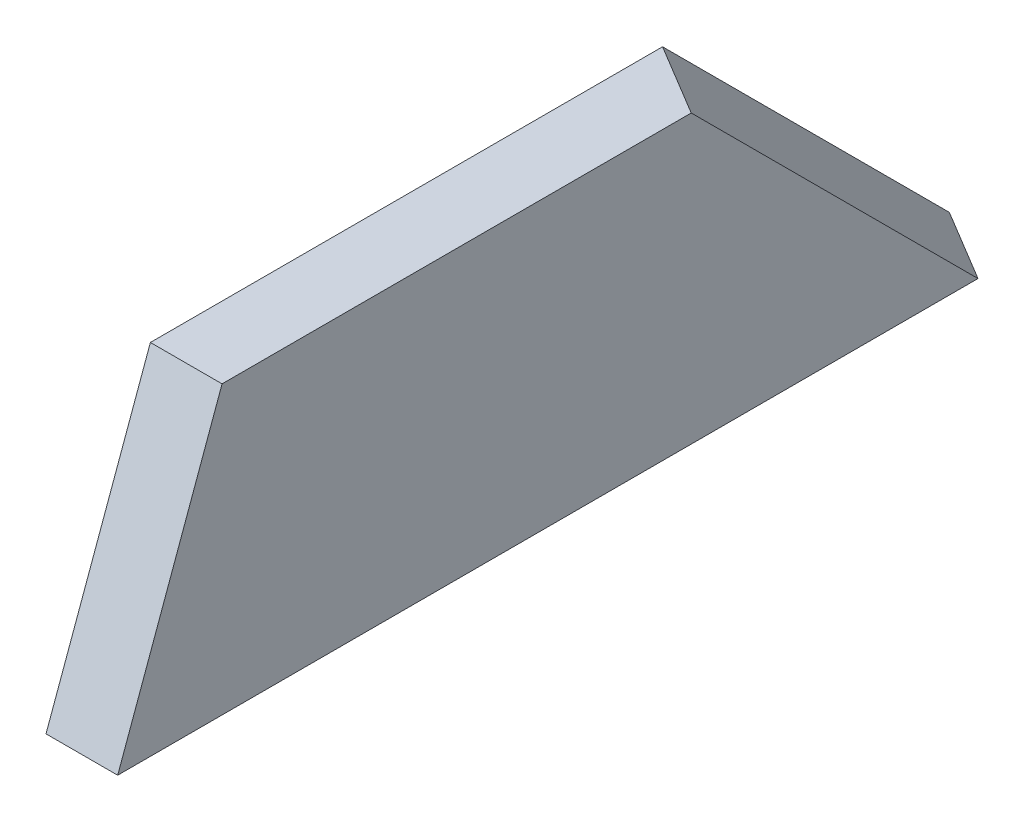
SolidWorks part; units mm, degrees
material "PE High Density"
ref_plane "Front Plane" through (0, 0, 0) normal (0, 0, 1) x (1, 0, 0)
ref_plane "Top Plane" through (0, 0, 0) normal (0, 1, 0) x (1, 0, 0)
ref_plane "Right Plane" through (0, 0, 0) normal (1, 0, 0) x (0, 0, -1)
sketch "Sketch1" plane through (0, 0, 0) normal (1, 0, 0) x (0, 0, -1)
  line L0 (-80.01, 0) -> (80.01, 0)
  line L1 (80.01, 0) -> (29.21, 50.8)
  line L3 (-61.5203, 50.8) -> (-80.01, 0)
  line L5 (29.21, 50.8) -> (-61.5203, 50.8)
  point P4 (0, 0)
  dimension "D1" = 45
  dimension "D2" = 160.02
  dimension "D3" = 50.8
  dimension "D4" = 70
extrude "Boss-Extrude1" add sketch "Sketch1" along normal blind 12.7
sketch "Sketch6" plane through (0, 0, 0) normal (0, -1, 0) x (1, 0, 0)
  line L0 (0, -80.01) -> (12.7, -80.01)
  line L1 (12.7, -80.01) -> (12.7, -72.39)
  line L2 (12.7, 80.01) -> (12.7, -80.01) construction
  line L3 (12.7, -72.39) -> (0, -80.01)
  dimension "D1" = 152.4
extrude "Cut-Extrude3" cut sketch "Sketch6" along direction (0, 0.7071, 0.7071) on the side against the normal up to surface (71.842 mm away)
